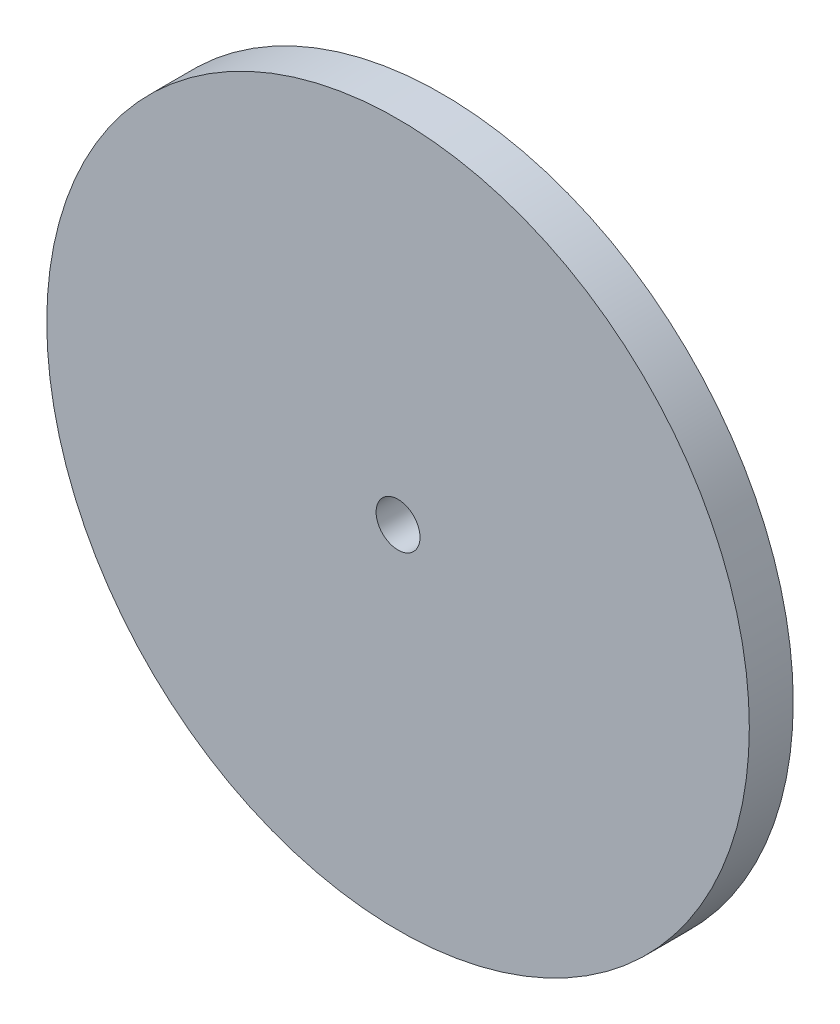
SolidWorks part; units mm, degrees
ref_plane "Front Plane" through (0, 0, 0) normal (0, 0, 1) x (1, 0, 0)
ref_plane "Top Plane" through (0, 0, 0) normal (0, 1, 0) x (1, 0, 0)
ref_plane "Right Plane" through (0, 0, 0) normal (1, 0, 0) x (0, 0, -1)
sketch "Sketch1" plane through (0, 0, 0) normal (0, 0, 1) x (1, 0, 0)
  circle A0 centre (0, 0) radius 50.8
  circle A1 centre (0, 0) radius 3.175
  dimension "D1" = 101.6
  dimension "D2" = 6.35
extrude "Boss-Extrude1" add sketch "Sketch1" along normal blind 6.35
